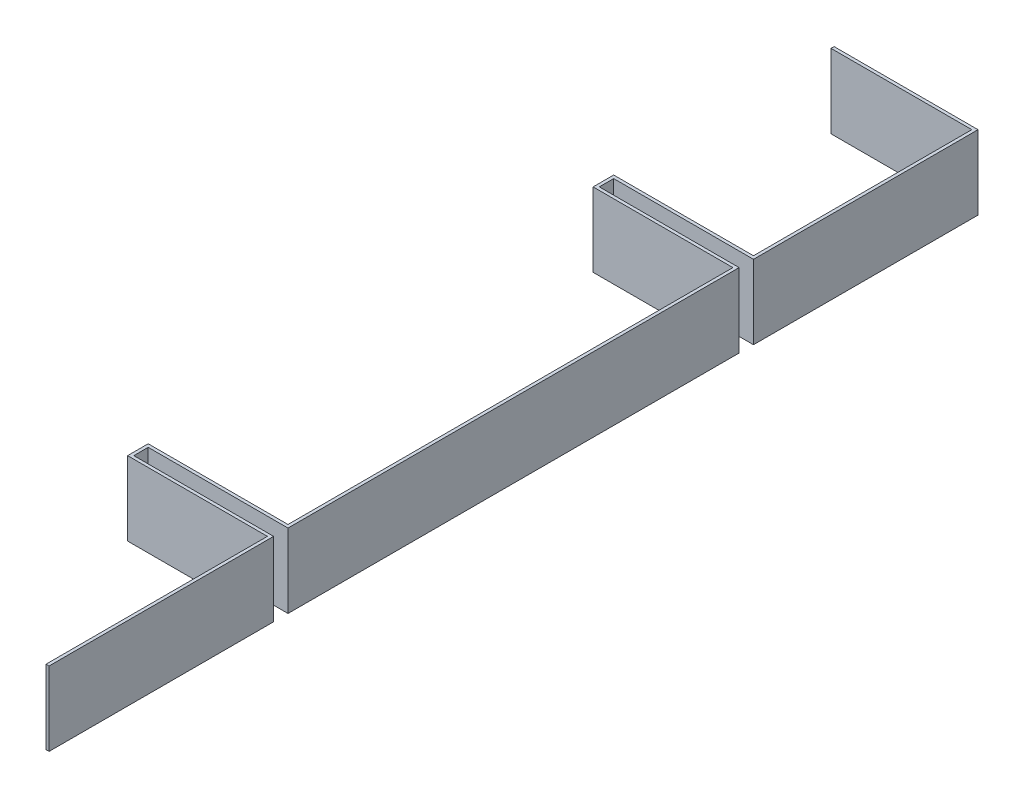
SolidWorks part; units mm, degrees
material "Pine"
ref_plane "Front Plane" through (0, 0, 0) normal (0, 0, 1) x (1, 0, 0)
ref_plane "Top Plane" through (0, 0, 0) normal (0, 1, 0) x (1, 0, 0)
ref_plane "Right Plane" through (0, 0, 0) normal (1, 0, 0) x (0, 0, -1)
sketch "Sketch1" plane through (0, 0, 0) normal (0, 1, 0) x (1, 0, 0)
  line L0 (0, 0) -> (0, 1386.84)
  line L1 (0, 1386.84) -> (-863.6, 1386.84)
  line L2 (-863.6, 1386.84) -> (-863.6, 1475.74)
  line L3 (-863.6, 1475.74) -> (0, 1475.74)
  line L4 (0, 1475.74) -> (0, 4262.12)
  line L5 (0, 4262.12) -> (-863.6, 4262.12)
  line L6 (-863.6, 4262.12) -> (-863.6, 4351.02)
  line L7 (-863.6, 4351.02) -> (0, 4351.02)
  line L8 (0, 4351.02) -> (0, 5737.86)
  line L11 (-19.05, 5718.81) -> (-19.05, 4370.07)
  line L12 (-19.05, 4370.07) -> (-882.65, 4370.07)
  line L13 (-882.65, 4370.07) -> (-882.65, 4243.07)
  line L14 (-882.65, 4243.07) -> (-19.05, 4243.07)
  line L15 (-19.05, 4243.07) -> (-19.05, 1494.79)
  line L16 (-19.05, 1494.79) -> (-882.65, 1494.79)
  line L17 (-882.65, 1494.79) -> (-882.65, 1367.79)
  line L18 (-882.65, 1367.79) -> (-19.05, 1367.79)
  line L19 (-19.05, 1367.79) -> (-19.05, 0)
  line L20 (-19.05, 0) -> (0, 0)
  line L21 (-863.6, 1431.29) -> (-882.65, 1431.29) construction
  line L22 (-431.8, 1386.84) -> (-431.8, 1367.79) construction
  line L23 (-19.05, 683.895) -> (0, 683.895) construction
  line L24 (-431.8, 1475.74) -> (-431.8, 1494.79) construction
  line L25 (-19.05, 2868.93) -> (0, 2868.93) construction
  line L26 (-431.8, 4262.12) -> (-431.8, 4243.07) construction
  line L27 (-863.6, 4306.57) -> (-882.65, 4306.57) construction
  line L28 (-450.85, 4370.07) -> (-450.85, 4351.02) construction
  line L29 (-19.05, 5044.44) -> (0, 5044.44) construction
  line L30 (0, 5737.86) -> (-889, 5737.86)
  line L31 (-889, 5737.86) -> (-889, 5718.81)
  line L32 (-889, 5718.81) -> (-19.05, 5718.81)
  dimension "D1" = 1386.84
  dimension "D2" = 2786.38
  dimension "D3" = 1386.84
  dimension "D4" = 88.9
  dimension "D5" = 88.9
  dimension "D6" = 863.6
  dimension "D7" = 863.6
  dimension "D8" = 19.05
  dimension "D9" = 889
extrude "Boss-Extrude1" add sketch "Sketch1" along normal blind 457.2
